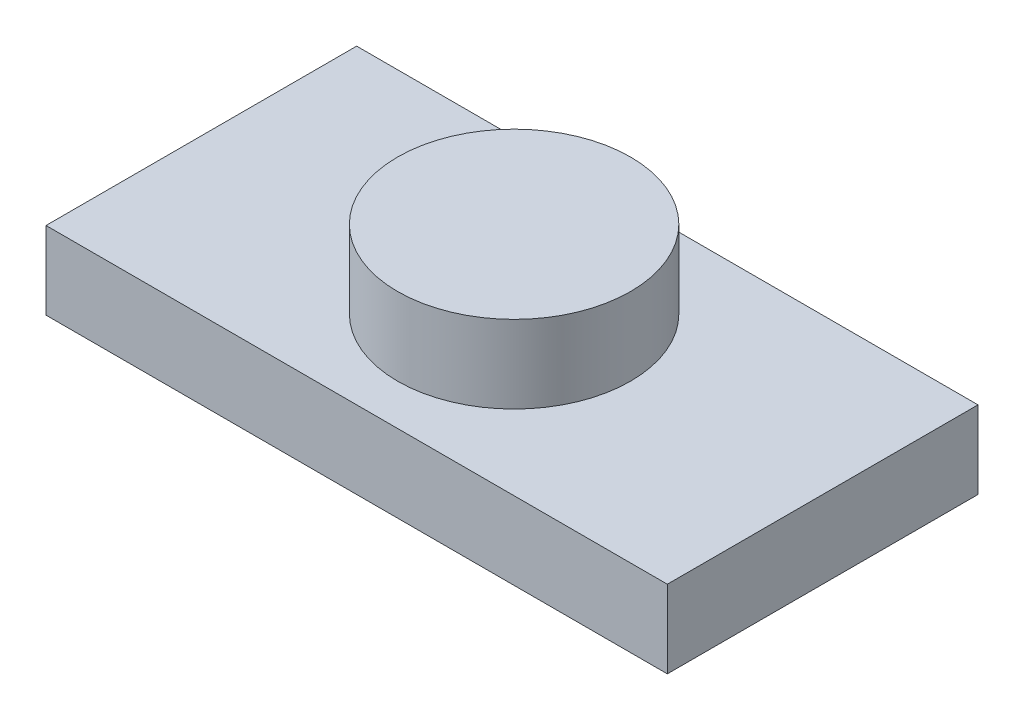
SolidWorks part; units mm, degrees
ref_plane "Front Plane" through (0, 0, 0) normal (0, 0, 1) x (1, 0, 0)
ref_plane "Top Plane" through (0, 0, 0) normal (0, 1, 0) x (1, 0, 0)
ref_plane "Right Plane" through (0, 0, 0) normal (1, 0, 0) x (0, 0, -1)
sketch "Sketch1" plane through (0, 0, 0) normal (0, 0, 1) x (1, 0, 0)
  line L1 (-20, 0.6221) -> (20, 0.6221)
  line L2 (-20, 0.6221) -> (-20, 5.6221)
  line L3 (-20, 5.6221) -> (20, 5.6221)
  line L4 (20, 0.6221) -> (20, 5.6221)
  point P0 (0, 0)
  dimension "Width" = 40
  dimension "Depth" = 5
extrude "Boss-Extrude2" add sketch "Sketch1" along normal blind 20
sketch "Sketch3" plane through (0, 5.6221, 0) normal (0, 1, 0) x (1, 0, 0)
  circle A0 centre (0, -9.8649) radius 7.5
  dimension "Diameter" = 15
extrude "Boss-Extrude3" add sketch "Sketch3" along normal blind 5
equation "\"A\" = \"A\""
equation "\"B\" = \"B\""
equation "\"C\"= 25"
equation "\"D\"= 10"
equation "\"E\"= 20"
equation "\"F\" = \"F\""
equation "\"Width@Sketch1\" = \"B\""
equation "\"Depth@Sketch1\"=\"A\""
equation "\"Diameter@Sketch3\"=\"F\""
equation "\"D1@Boss-Extrude3\"=\"A\""
